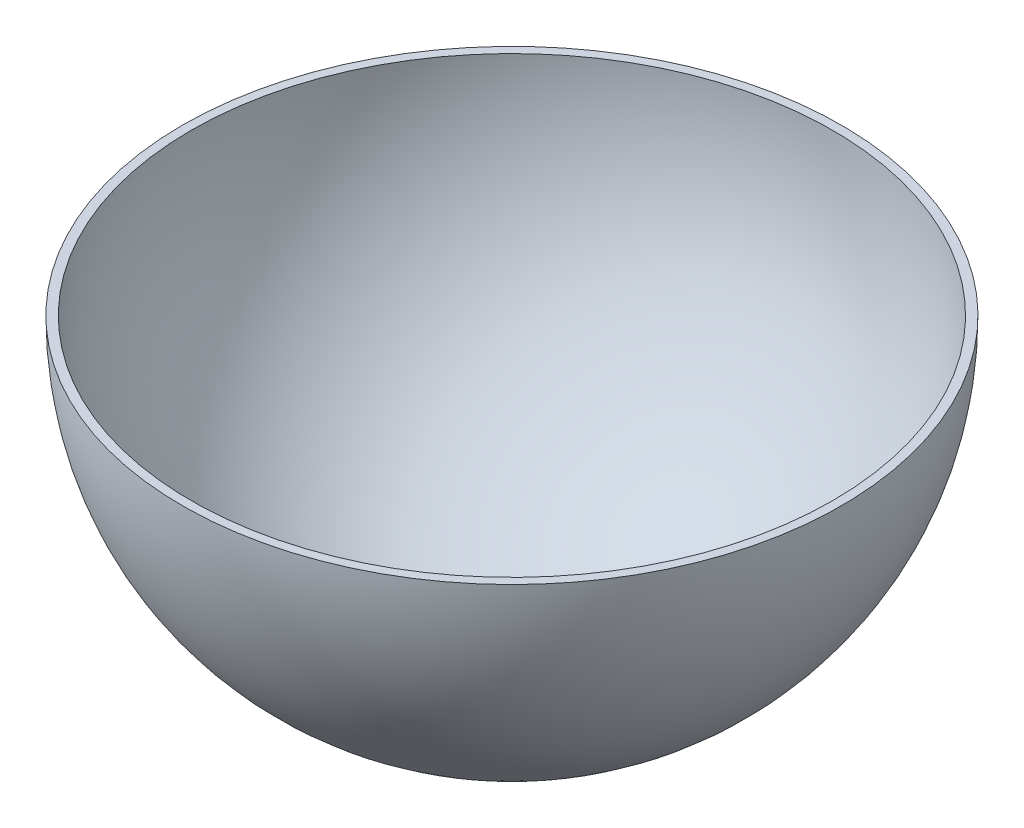
SolidWorks part; units mm, degrees
ref_plane "前视基准面" through (0, 0, 0) normal (0, 0, 1) x (1, 0, 0)
ref_plane "上视基准面" through (0, 0, 0) normal (0, 1, 0) x (1, 0, 0)
ref_plane "右视基准面" through (0, 0, 0) normal (1, 0, 0) x (0, 0, -1)
sketch "草图1" plane through (0, 0, 0) normal (0, 0, 1) x (1, 0, 0)
  line L0 (0, 0) -> (75, 0)
  line L1 (0, 0) -> (0, -74.2464)
  line L2 (0, -74.2464) -> (10.6051, -74.2464)
  arc A0 (10.6051, -74.2464) -> (75, 0) centre (0, 0) ccw
  dimension "D1" = 150
revolve "旋转1" add sketch "草图1" angle 360 about L1
sketch "草图2" plane through (0, 0, 0) normal (0, 0, 1) x (1, 0, 0)
  circle A0 centre (0, 0) radius 74
  dimension "D1" = 148
shell "抽壳1" thickness 2
